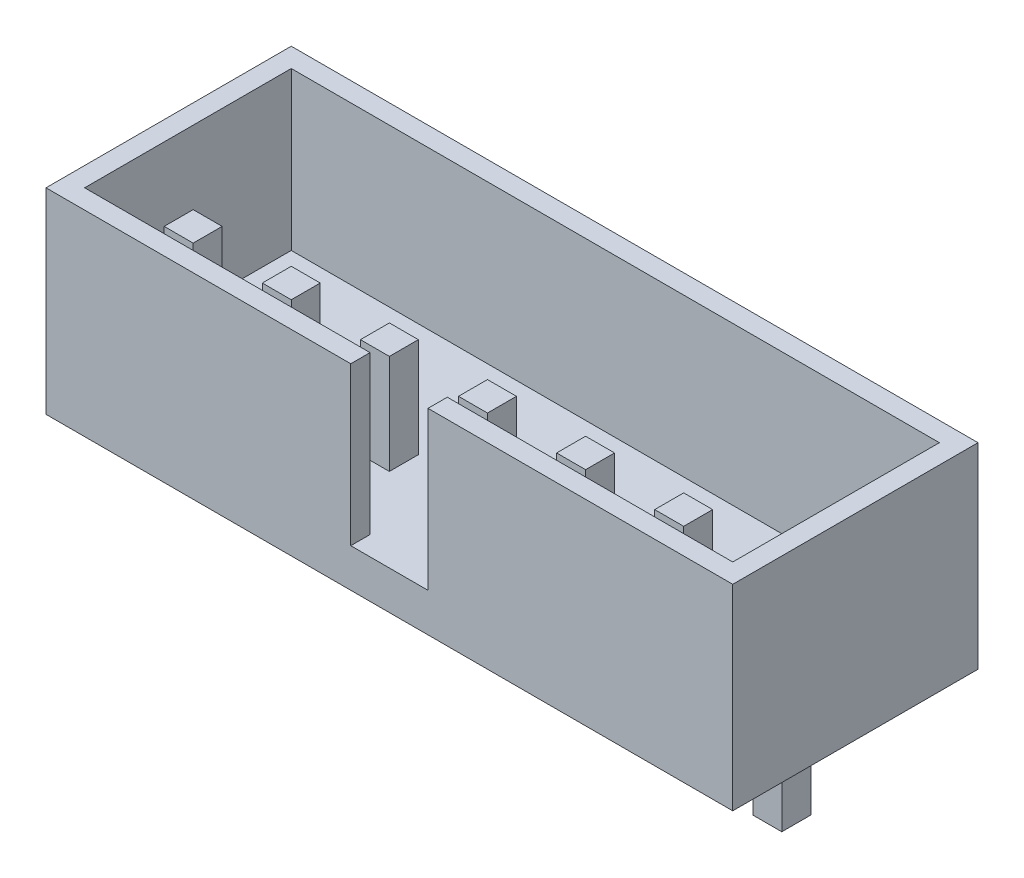
SolidWorks part; units mm, degrees
ref_plane "前视基准面" through (0, 0, 0) normal (0, 0, 1) x (1, 0, 0)
ref_plane "上视基准面" through (0, 0, 0) normal (0, 1, 0) x (1, 0, 0)
ref_plane "右视基准面" through (0, 0, 0) normal (1, 0, 0) x (0, 0, -1)
sketch "草图1" plane through (0, 0, 0) normal (0, 1, 0) x (1, 0, 0)
  line L0 (0, 7.1914) -> (0, -5.4429) construction
  line L1 (-8.89, 3.175) -> (8.89, 3.175)
  line L2 (-8.89, 3.175) -> (-8.89, -3.175)
  line L3 (-8.89, -3.175) -> (8.89, -3.175)
  line L4 (8.89, 3.175) -> (8.89, -3.175)
  line L5 (-10.6234, 0) -> (16.1963, 0) construction
  dimension "D1" = 17.78
  dimension "D2" = 6.35
extrude "拉伸1" add sketch "草图1" along normal blind 5.08
sketch "草图2" plane through (0, 5.08, 0) normal (0, 1, 0) x (-1, 0, 0)
  line L8 (8.39, -2.675) -> (8.39, 2.675)
  line L9 (8.39, 2.675) -> (-8.39, 2.675)
  line L10 (-8.39, 2.675) -> (-8.39, -2.675)
  line L11 (-8.39, -2.675) -> (8.39, -2.675)
  line L12 (8.39, -2.675) -> (8.39, 2.675)
  line L13 (8.39, 2.675) -> (-8.39, 2.675)
  line L14 (-8.39, 2.675) -> (-8.39, -2.675)
  line L15 (-8.39, -2.675) -> (8.39, -2.675)
  dimension "D1" = 0.5
extrude "切除-拉伸1" cut sketch "草图2" against normal offset from surface (4.08 mm away) 1 up to face at (0, 0, 0)
sketch "草图3" plane through (0, 0, 3.175) normal (0, 0, 1) x (1, 0, 0)
  line L0 (-8.89, 5.08) -> (8.89, 5.08) construction
  line L1 (-1, 5.08) -> (1, 5.08)
  line L2 (-1, 5.08) -> (-1, 1)
  line L3 (-1, 1) -> (1, 1)
  line L4 (1, 5.08) -> (1, 1)
  line L5 (8.39, 1) -> (-8.39, 1) construction
  line L6 (0, -1.5083) -> (0, 12.2426) construction
  dimension "D1" = 2
extrude "切除-拉伸2" cut sketch "草图3" against normal blind 1
sketch "草图4" plane through (0, 0, 0) normal (0, -1, 0) x (1, 0, 0)
  line L0 (7.6775, 0.635) -> (-8.5467, 0.635) construction
  line L1 (4.705, 1.01) -> (5.455, 1.01)
  line L2 (0, -3.6953) -> (0, 4.0669) construction
  line L3 (0, 2.1009) -> (0, -0.7012) construction
  line L4 (-0.375, 1.01) -> (0.375, 1.01)
  line L5 (-0.375, 1.01) -> (-0.375, 0.26)
  line L6 (-0.375, 0.26) -> (0.375, 0.26)
  line L7 (0.375, 1.01) -> (0.375, 0.26)
  line L8 (2.165, 1.01) -> (2.915, 1.01)
  line L9 (2.165, 1.01) -> (2.165, 0.26)
  line L10 (2.165, 0.26) -> (2.915, 0.26)
  line L11 (2.915, 1.01) -> (2.915, 0.26)
  line L12 (4.705, 1.01) -> (4.705, 0.26)
  line L13 (4.705, 0.26) -> (5.455, 0.26)
  line L14 (5.455, 1.01) -> (5.455, 0.26)
  line L15 (7.245, 1.01) -> (7.995, 1.01)
  line L16 (-2.915, 1.01) -> (-2.165, 1.01)
  line L17 (-2.915, 1.01) -> (-2.915, 0.26)
  line L18 (-2.915, 0.26) -> (-2.165, 0.26)
  line L19 (-2.165, 1.01) -> (-2.165, 0.26)
  line L20 (4.705, 1.01) -> (5.455, 1.01) [skipped]
  line L21 (4.705, 1.01) -> (4.705, 0.26) [skipped]
  line L22 (4.705, 0.26) -> (5.455, 0.26) [skipped]
  line L23 (5.455, 1.01) -> (5.455, 0.26) [skipped]
  line L24 (7.245, 1.01) -> (7.245, 0.26)
  line L25 (7.245, 0.26) -> (7.995, 0.26)
  line L26 (7.995, 1.01) -> (7.995, 0.26)
  line L27 (-7.995, 1.01) -> (-7.995, 0.26)
  line L28 (-7.245, 0.26) -> (-7.995, 0.26)
  line L29 (-7.245, 1.01) -> (-7.245, 0.26)
  line L30 (-7.245, 1.01) -> (-7.995, 1.01)
  line L31 (-5.455, 1.01) -> (-5.455, 0.26)
  line L32 (-4.705, 0.26) -> (-5.455, 0.26)
  line L33 (-4.705, 1.01) -> (-4.705, 0.26)
  line L34 (-4.705, 1.01) -> (-5.455, 1.01)
  dimension "D1" = 3
  dimension "D2" = 0.75
  dimension "D3" = 0.75
  dimension "D4" = 0
extrude "拉伸2" add sketch "草图4" along normal blind 2 and the other way offset from surface (3.58 mm away) 1.5 other way up to face at (0, 5.08, 0.975)
